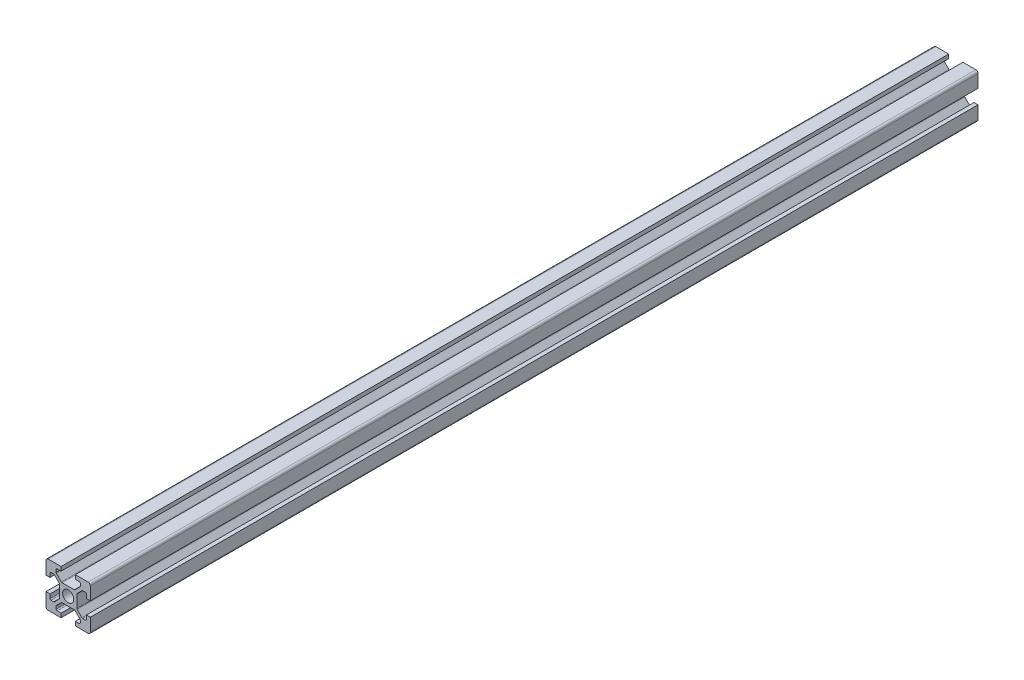
SolidWorks part; units mm, degrees
material "1060 Alloy"
ref_plane "Front Plane" through (0, 0, 0) normal (0, 0, 1) x (1, 0, 0)
ref_plane "Top Plane" through (0, 0, 0) normal (0, 1, 0) x (1, 0, 0)
ref_plane "Right Plane" through (0, 0, 0) normal (1, 0, 0) x (0, 0, -1)
sketch "Sketch1" plane through (0, 0, 0) normal (0, 0, 1) x (1, 0, 0)
  line L0 (20, 0) -> (-8.059, 28.059) construction
  line L1 (0, 0) -> (6.8, 0)
  line L2 (0, 0) -> (0, 6.8)
  line L3 (0, 20) -> (6.8, 20)
  line L4 (20, 0) -> (20, 6.8)
  line L5 (6.8, 20) -> (6.8, 18.2)
  line L6 (20, 20) -> (8.2322, 8.2322) construction
  line L7 (12.95, 6.1) -> (7.05, 6.1)
  line L8 (13.9, 7.05) -> (13.9, 12.95)
  line L9 (12.95, 13.9) -> (7.05, 13.9)
  line L10 (6.1, 7.05) -> (6.1, 12.95)
  line L11 (13.9, 6.1) -> (6.1, 13.9) construction
  line L12 (13.9, 13.9) -> (6.1, 6.1) construction
  line L13 (4.55, 16.4) -> (7.05, 13.9)
  line L14 (13.2, 18.2) -> (13.2, 20)
  line L15 (1.8, 6.8) -> (0, 6.8)
  line L16 (0, 13.2) -> (0, 20)
  line L17 (0, 13.2) -> (1.8, 13.2)
  line L18 (10, 10) -> (10, 13.9) construction
  line L19 (16.4, 4.55) -> (13.9, 7.05)
  line L20 (4.55, 16.4) -> (4.55, 18.2)
  line L21 (4.55, 18.2) -> (6.8, 18.2)
  line L22 (13.2, 18.2) -> (15.45, 18.2)
  line L23 (15.45, 18.2) -> (15.45, 16.4)
  line L24 (15.45, 16.4) -> (12.95, 13.9)
  line L25 (16.4, 4.55) -> (18.2, 4.55)
  line L26 (18.2, 4.55) -> (18.2, 6.8)
  line L27 (20, 6.8) -> (18.2, 6.8)
  line L28 (18.2, 13.2) -> (20, 13.2)
  line L29 (18.2, 13.2) -> (18.2, 15.45)
  line L30 (18.2, 15.45) -> (16.4, 15.45)
  line L31 (16.4, 15.45) -> (13.9, 12.95)
  line L32 (1.8, 4.55) -> (3.6, 4.55)
  line L33 (3.6, 15.45) -> (6.1, 12.95)
  line L34 (3.6, 15.45) -> (1.8, 15.45)
  line L35 (1.8, 15.45) -> (1.8, 13.2)
  line L36 (0, 13.2) -> (1.8, 13.2)
  line L37 (1.8, 6.8) -> (0, 6.8)
  line L38 (3.6, 4.55) -> (6.1, 7.05)
  line L39 (1.8, 6.8) -> (1.8, 4.55)
  line L40 (15.45, 3.6) -> (12.95, 6.1)
  line L41 (4.55, 3.6) -> (7.05, 6.1)
  line L42 (4.55, 1.8) -> (4.55, 3.6)
  line L43 (6.8, 1.8) -> (4.55, 1.8)
  line L44 (6.8, 1.8) -> (6.8, 0)
  line L45 (15.45, 3.6) -> (15.45, 1.8)
  line L46 (15.45, 1.8) -> (13.2, 1.8)
  line L47 (13.2, 0) -> (13.2, 1.8)
  line L48 (13.2, 20) -> (20, 20)
  line L49 (20, 13.2) -> (20, 20)
  line L50 (13.2, 0) -> (20, 0)
  line L51 (6.1, 6.1) -> (-5.5045, -5.5045) construction
  circle A0 centre (10, 10) radius 2.5
  point P25 (10, 16.4)
  point P39 (13.2, 19.1)
  point P46 (0.9, 6.8)
  dimension "D3" = 5
  dimension "D2" = 20
  dimension "D4" = 7.8
  dimension "D5" = 7.8
  dimension "D6" = 6.8
  dimension "D7" = 6.8
  dimension "D8" = 1.8
  dimension "D9" = 10.9
  dimension "D10" = 1.8
  dimension "D11" = 10.9
  dimension "D12" = 20
extrude "Boss-Extrude1" add sketch "Sketch1" along normal blind 400 contours L47 L50 L4 L27 L26 L25 L19 L8 L31 L30 L29 L28 L49 L48 L14 L22 L23 L24 L9 L13 L20 L21 L5 L3 L16 L17 L35 L34 L33 L10 L38 L32 L39 L15 L2 L1 L44 L43 L42 L41 L7 L40 L45 L46 A0
fillet "Fillet1" radius 1 4 edges at (20, 20, 200) (20, 0, 200) (0, 0, 200) (0, 20, 200)
fillet "Fillet2" radius 0.5 6 edges at (4.55, 18.2, 200) (4.55, 16.4, 200) (7.05, 13.9, 200) (15.45, 18.2, 200) (15.45, 16.4, 200) (12.95, 13.9, 200)
fillet "Fillet3" radius 0.5 6 edges at (18.2, 15.45, 200) (16.4, 15.45, 200) (13.9, 12.95, 200) (18.2, 4.55, 200) (13.9, 7.05, 200) (16.4, 4.55, 200)
fillet "Fillet4" radius 0.5 6 edges at (1.8, 15.45, 200) (3.6, 15.45, 200) (6.1, 12.95, 200) (3.6, 4.55, 200) (1.8, 4.55, 200) (6.1, 7.05, 200)
fillet "Fillet5" radius 0.5 6 edges at (7.05, 6.1, 200) (4.55, 3.6, 200) (4.55, 1.8, 200) (15.45, 1.8, 200) (15.45, 3.6, 200) (12.95, 6.1, 200)
sketch "Sketch2" plane through (0, 24, 0) normal (0, 1, 0) x (1, 0, 0)
  circle A0 centre (10, -10) radius 2.5
  circle A1 centre (10, -390) radius 2.5
extrude "Cut-Extrude1" cut sketch "Sketch2" against normal up to surface (17.9 mm away) up to face at (10, 6.1, 200)
